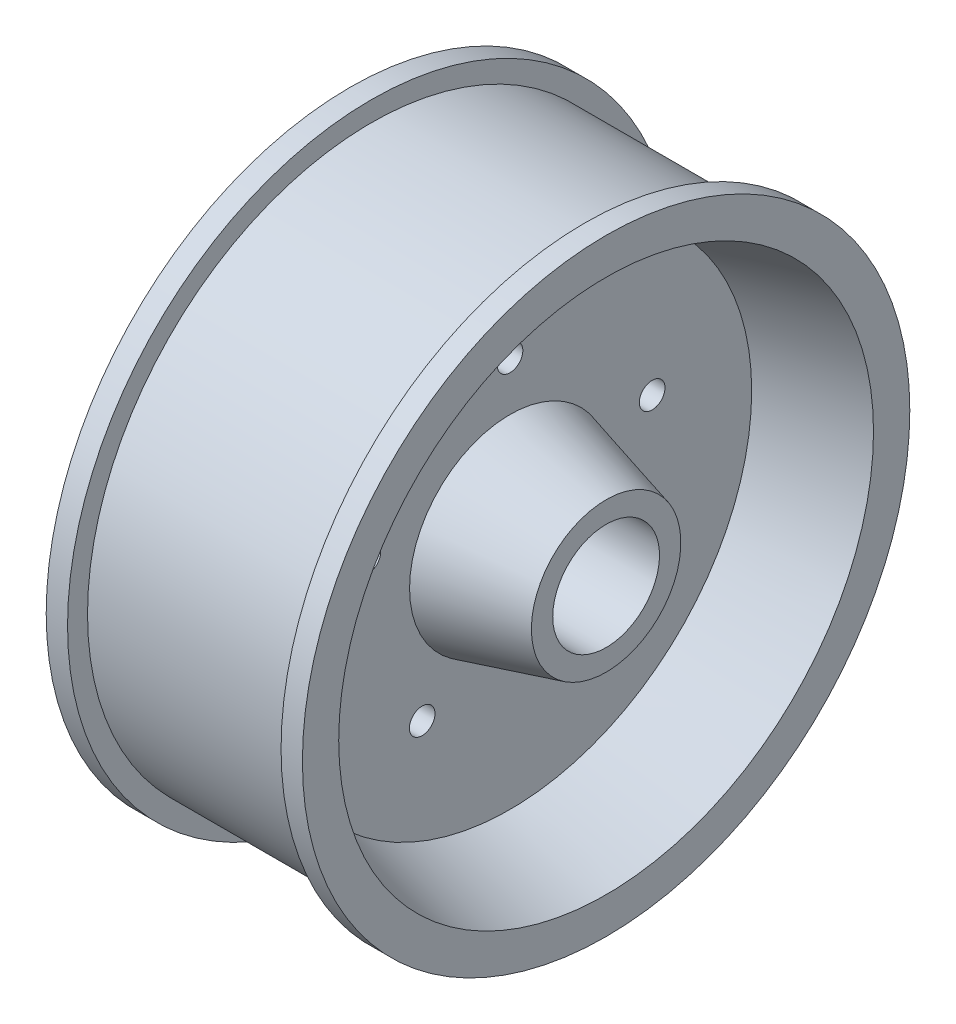
SolidWorks part; units mm, degrees
material "AISI 304"
ref_plane "Front Plane" through (0, 0, 0) normal (0, 0, 1) x (1, 0, 0)
ref_plane "Top Plane" through (0, 0, 0) normal (0, 1, 0) x (1, 0, 0)
ref_plane "Right Plane" through (0, 0, 0) normal (1, 0, 0) x (0, 0, -1)
sketch "Sketch1" plane through (0, 0, 0) normal (0, 0, 1) x (1, 0, 0)
  line L0 (-1499.6566, 0) -> (73483.1756, 0) construction
  line L1 (0, -1499.6566) -> (0, 73483.1756) construction
  line L2 (38.1, 15.875) -> (-38.1, 15.875)
  line L3 (-38.1, 15.875) -> (-38.1, 22.225)
  line L4 (-38.1, 22.225) -> (-9.525, 29.8816)
  line L5 (-9.525, 29.8816) -> (-9.525, 71.8708)
  line L6 (-9.525, 71.8708) -> (-38.1, 79.5274)
  line L7 (-38.1, 79.5274) -> (-38.1, 90.3224)
  line L8 (-38.1, 90.3224) -> (-31.75, 90.3224)
  line L9 (-31.75, 90.3224) -> (-31.75, 84.3807)
  line L10 (-31.75, 84.3807) -> (31.75, 84.3807)
  line L11 (-38.1, 79.5274) -> (-38.1, 22.225)
  line L12 (9.525, 71.8708) -> (38.1, 79.5274)
  line L13 (9.525, 29.8816) -> (9.525, 71.8708)
  line L14 (38.1, 22.225) -> (9.525, 29.8816)
  line L15 (38.1, 15.875) -> (38.1, 22.225)
  line L16 (38.1, 79.5274) -> (38.1, 22.225)
  line L17 (38.1, 79.5274) -> (38.1, 90.3224)
  line L18 (38.1, 90.3224) -> (31.75, 90.3224)
  line L19 (31.75, 90.3224) -> (31.75, 84.3807)
  line L20 (-38.1, -15.875) -> (-38.1, -22.225)
  line L21 (38.1, -15.875) -> (38.1, -22.225)
  line L22 (38.1, -15.875) -> (-38.1, -15.875)
  line L23 (-38.1, -22.225) -> (-9.525, -29.8816)
  line L24 (38.1, -22.225) -> (9.525, -29.8816)
  line L25 (-9.525, -29.8816) -> (-9.525, -71.8708)
  line L26 (9.525, -29.8816) -> (9.525, -71.8708)
  line L27 (38.1, -79.5274) -> (38.1, -22.225)
  line L28 (-38.1, -79.5274) -> (-38.1, -22.225)
  line L29 (-9.525, -71.8708) -> (-38.1, -79.5274)
  line L30 (9.525, -71.8708) -> (38.1, -79.5274)
  line L31 (38.1, -79.5274) -> (38.1, -90.3224)
  line L32 (38.1, -90.3224) -> (31.75, -90.3224)
  line L33 (-31.75, -90.3224) -> (-31.75, -84.3807)
  line L34 (-38.1, -90.3224) -> (-31.75, -90.3224)
  line L35 (-31.75, -84.3807) -> (31.75, -84.3807)
  line L36 (31.75, -90.3224) -> (31.75, -84.3807)
  line L37 (-38.1, -79.5274) -> (-38.1, -90.3224)
  line L38 (-38.1, 15.875) -> (-38.1, -15.875)
  line L39 (38.1, 15.875) -> (38.1, -15.875)
  point P15 (38.1, 50.8762)
  point P20 (0, 15.875)
  point P23 (0, 84.3807)
  dimension "D1" = 57.3024
  dimension "D2" = 6.35
  dimension "D3" = 10.795
  dimension "D4" = 6.35
  dimension "D5" = 19.05
  dimension "D6" = 15
  dimension "D7" = 15
  dimension "D8" = 31.75
  dimension "D9" = 38.1
revolve "Revolve2" add sketch "Sketch1" angle 360 about L0
sketch "Sketch2" plane through (9.525, 0, 0) normal (1, 0, 0) x (0, 0, -1)
  circle A0 centre (0, 0) radius 44.45 construction
  circle A1 centre (0, 44.45) radius 3.81
  dimension "D1" = 88.9
  dimension "D2" = 7.62
extrude "Cut-Extrude1" cut sketch "Sketch2" against normal through all
pattern_circular "CirPattern1" count 5 over 360 about axis through (0, 0, 0) along (1, 0, 0) of "Cut-Extrude1"
